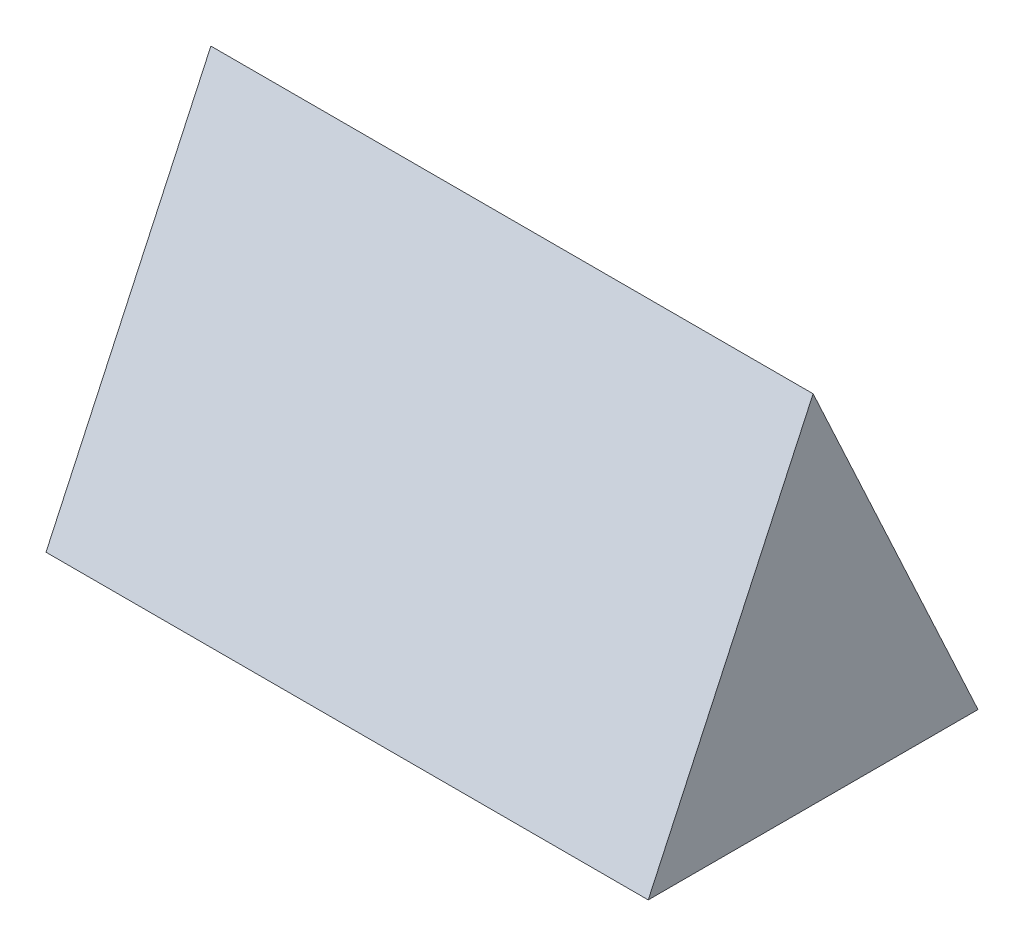
SolidWorks part; units mm, degrees
ref_plane "Front Plane" through (0, 0, 0) normal (0, 0, 1) x (1, 0, 0)
ref_plane "Top Plane" through (0, 0, 0) normal (0, 1, 0) x (1, 0, 0)
ref_plane "Right Plane" through (0, 0, 0) normal (1, 0, 0) x (0, 0, -1)
sketch "Sketch1" plane through (0, 0, 0) normal (0, 0, 1) x (1, 0, 0)
  line L0 (-185.3412, -69.1215) -> (164.6588, -69.1215)
  line L1 (-185.3412, -69.1215) -> (-185.3412, -31.0215)
  line L2 (164.6588, -69.1215) -> (164.6588, -31.0215)
  line L3 (-185.3412, -31.0215) -> (-147.2412, -31.0215)
  line L4 (164.6588, -31.0215) -> (81.5588, -31.0215)
  line L5 (-147.2412, -69.1215) -> (-147.2412, 130.8785)
  line L6 (119.6088, -31.0215) -> (164.6588, -31.0215) construction
  line L7 (144.6588, -31.0215) -> (144.6588, -13.3431) construction
  line L9 (74.0588, 17.0285) -> (74.0588, -38.5215)
  line L10 (74.0588, -38.5215) -> (89.0588, -38.5215)
  line L11 (89.0588, 17.0285) -> (89.0588, -38.5215)
  line L12 (74.0588, 17.0285) -> (89.0588, 17.0285)
  line L13 (-94.1412, -31.0215) -> (-94.1412, -25.0741)
  line L14 (-94.1412, -31.0215) -> (-94.1412, -25.0741)
  line L15 (-94.1412, -31.0215) -> (-109.1412, -31.0215) construction
  line L16 (23.5088, -33.5215) -> (33.7425, -33.5215)
  line L18 (-94.1412, -25.0741) -> (23.7602, -25.0741)
  line L19 (33.7425, -33.5215) -> (23.7602, -33.5215)
  line L20 (-94.1412, -31.0215) -> (-94.1412, -33.5215)
  line L21 (81.5588, -31.0215) -> (81.5588, 7.0285) construction
  line L22 (-94.1412, -33.5215) -> (23.5088, -33.5215)
  line L23 (33.7425, -33.5215) -> (33.7425, 68.7807)
  line L24 (33.7425, 68.7807) -> (23.7602, 68.7807)
  line L25 (23.7602, -33.5215) -> (23.7602, 68.7807)
  circle A0 centre (-147.2412, -31.0215) radius 38.1
  circle A2 centre (81.5588, -31.0215) radius 38.05
  arc A3 (74.0588, 25.3222) -> (23.7602, -25.0741) centre (75.7808, -26.6953) ccw
  point P14 (81.5588, 17.0285)
  dimension "D7" = 117.65
  dimension "D1" = 350
  dimension "D2" = 38.1
  dimension "D3" = 38.1
  dimension "D4" = 38.1
  dimension "D5" = 83.1
  dimension "D6" = 200
  dimension "D8" = 45.05
  dimension "D9" = 7.5
  dimension "D10" = 7.5
  dimension "D11" = 7.5
  dimension "D12" = 45.05
  dimension "D13" = 25.05
  dimension "D14" = 20
  dimension "D15" = 15
  dimension "D17" = 10
sketch "Sketch2" plane through (0, 0, 0) normal (1, 0, 0) x (0, 0, -1)
  line L0 (0, -31.0215) -> (-75, -31.0215)
  line L1 (0, 7.0785) -> (0, -69.1215) construction
  line L2 (0, -31.0215) -> (75, -31.0215)
  line L3 (0, 130.8785) -> (-75, -31.0215)
  line L4 (0, -69.1215) -> (0, 130.8785) construction
  line L5 (0, 130.8785) -> (75, -31.0215)
  dimension "D1" = 75
  dimension "D2" = 75
extrude "Boss-Extrude2" add sketch "Sketch2" along normal blind 126.95 and the other way blind 147
